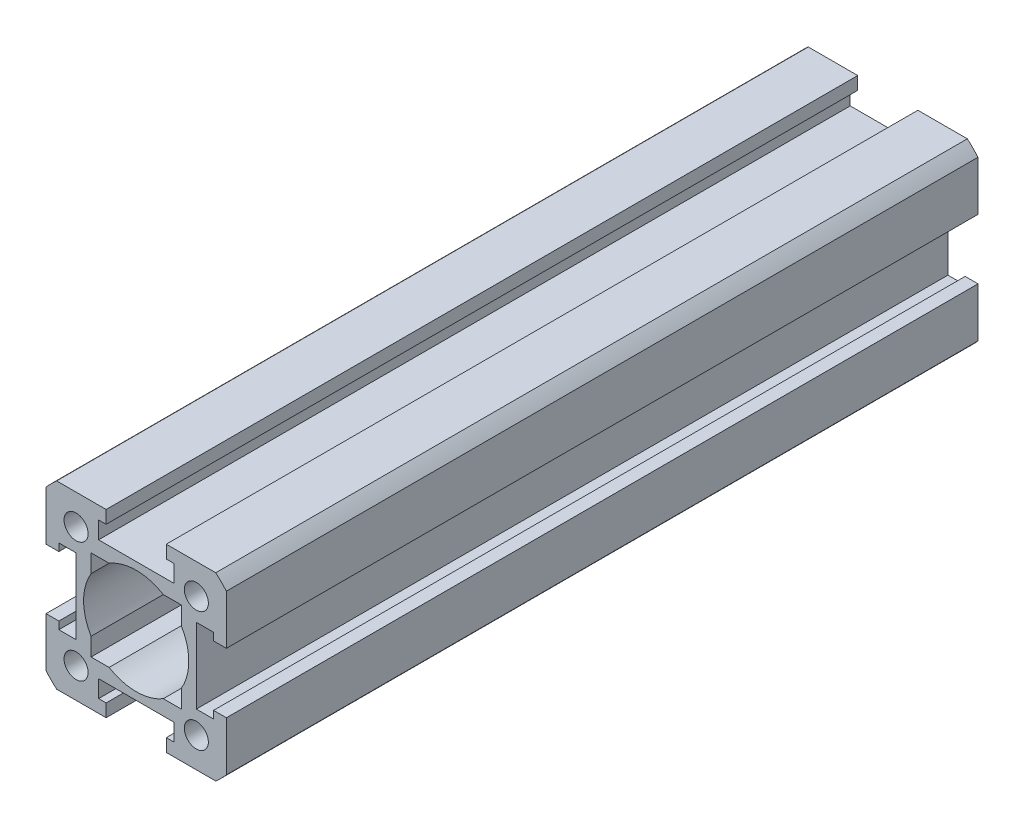
SolidWorks part; units mm, degrees
ref_plane "Front Plane" through (0, 0, 0) normal (0, 0, 1) x (1, 0, 0)
ref_plane "Top Plane" through (0, 0, 0) normal (0, 1, 0) x (1, 0, 0)
ref_plane "Right Plane" through (0, 0, 0) normal (1, 0, 0) x (0, 0, -1)
sketch "Sketch1" plane through (0, 0, 0) normal (0, 0, 1) x (1, 0, 0)
  line L0 (0, 0) -> (19.7206, 19.7206) construction
  line L1 (0, 0) -> (27.6112, 0) construction
  line L2 (0, 10.2912) -> (0, 0) construction
  line L3 (-8, -8) -> (8, -8)
  line L4 (-8, -8) -> (-8, 8)
  line L5 (-8, 8) -> (8, 8)
  line L6 (8, -8) -> (8, 8)
  line L7 (-8, -8) -> (8, 8) construction
  line L8 (-8, 8) -> (8, -8) construction
  line L9 (-12, -12) -> (12, -12)
  line L10 (-12, -12) -> (-12, 12)
  line L11 (-12, 12) -> (12, 12)
  line L12 (12, -12) -> (12, 12)
  line L13 (-12, -12) -> (12, 12) construction
  line L14 (-12, 12) -> (12, -12) construction
  line L15 (-6, -6) -> (6, -6)
  line L16 (-6, -6) -> (-6, 6)
  line L17 (-6, 6) -> (6, 6)
  line L18 (6, -6) -> (6, 6)
  line L19 (-6, -6) -> (6, 6) construction
  line L20 (-6, 6) -> (6, -6) construction
  line L21 (0, 0) -> (0, 10.2912) construction
  line L22 (-4, 12) -> (4, 12)
  line L23 (-4, 12) -> (-4, 10.2912)
  line L24 (-4, 10.2912) -> (4, 10.2912)
  line L25 (4, 12) -> (4, 10.2912)
  line L26 (-5, 10.2912) -> (5, 10.2912)
  line L27 (-5, 10.2912) -> (-5, 8)
  line L28 (-5, 8) -> (5, 8)
  line L29 (5, 10.2912) -> (5, 8)
  line L30 (12, 4) -> (12, -4)
  line L31 (12, 4) -> (10.2912, 4)
  line L32 (10.2912, 4) -> (10.2912, -4)
  line L33 (12, -4) -> (10.2912, -4)
  line L34 (10.2912, 5) -> (10.2912, -5)
  line L35 (10.2912, 5) -> (8, 5)
  line L36 (8, 5) -> (8, -5)
  line L37 (10.2912, -5) -> (8, -5)
  line L38 (4, -12) -> (-4, -12)
  line L39 (4, -12) -> (4, -10.2912)
  line L40 (4, -10.2912) -> (-4, -10.2912)
  line L41 (-4, -12) -> (-4, -10.2912)
  line L42 (5, -10.2912) -> (-5, -10.2912)
  line L43 (5, -10.2912) -> (5, -8)
  line L44 (5, -8) -> (-5, -8)
  line L45 (-5, -10.2912) -> (-5, -8)
  line L46 (-12, -4) -> (-12, 4)
  line L47 (-12, -4) -> (-10.2912, -4)
  line L48 (-10.2912, -4) -> (-10.2912, 4)
  line L49 (-12, 4) -> (-10.2912, 4)
  line L50 (-10.2912, -5) -> (-10.2912, 5)
  line L51 (-10.2912, -5) -> (-8, -5)
  line L52 (-8, -5) -> (-8, 5)
  line L53 (-10.2912, 5) -> (-8, 5)
  line L54 (-8, 0) -> (0, 0) construction
  circle A0 centre (0, 0) radius 16
  circle A1 centre (0, 0) radius 7
  circle A2 centre (8, 8) radius 1.6
  circle A3 centre (8, -8) radius 1.6
  circle A4 centre (-8, -8) radius 1.6
  circle A5 centre (-8, 8) radius 1.6
  dimension "D1" = 32
  dimension "D2" = 14
  dimension "D7" = 3.2
  dimension "D3" = 45
  dimension "D4" = 16
  dimension "D5" = 24
  dimension "D8" = 12
  dimension "D9" = 8
  dimension "D10" = 10
  dimension "D6" = 4
  dimension "D11" = 4
extrude "Boss-Extrude1" add sketch "Sketch1" along normal blind 100 contours A5 L5 L27 L26 L23 L11 A0 L10 L49 L50 L53 L4 | A2 L6 L35 L34 L31 L12 A0 L11 L25 L26 L29 L5 | A5 L4 A4 L3 A3 L6 A2 L5 A1 L17 L18 L15 L16 | A3 L3 L43 L42 L39 L9 A0 L12 L33 L34 L37 L6 | A4 L4 L51 L50 L47 L10 A0 L9 L41 L42 L45 L3
